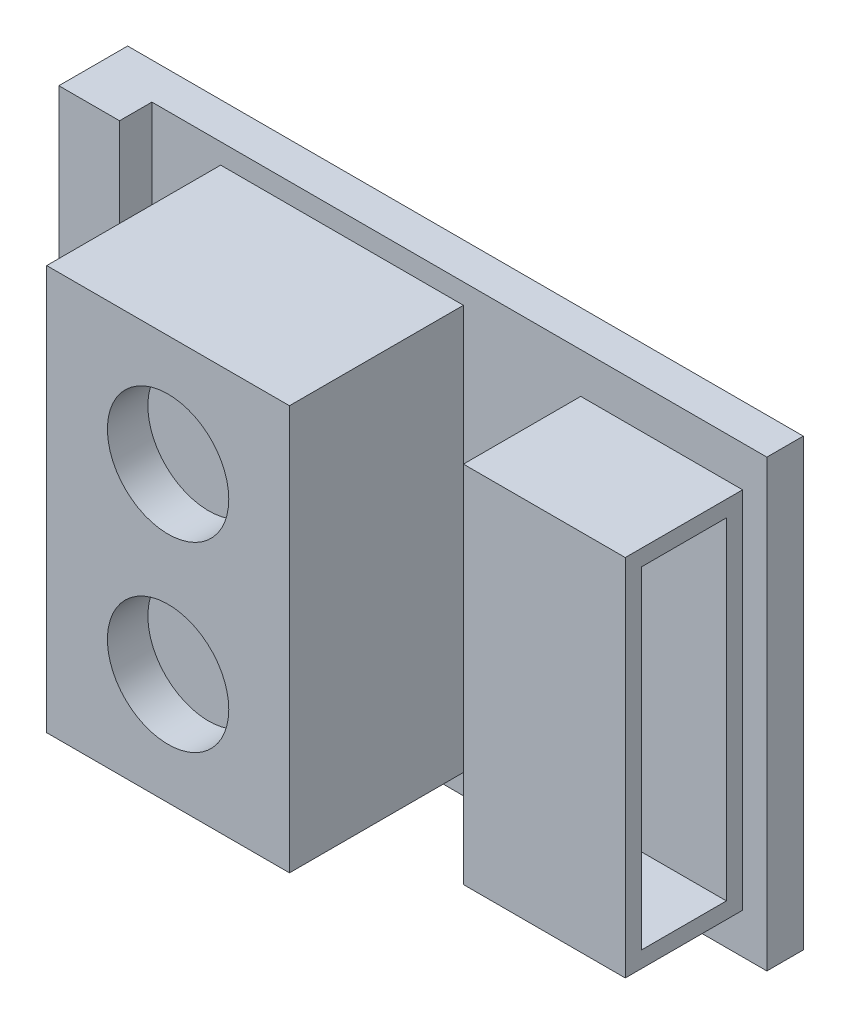
SolidWorks part; units mm, degrees
ref_plane "Plano frontal" through (0, 0, 0) normal (0, 0, 1) x (1, 0, 0)
ref_plane "Plano superior" through (0, 0, 0) normal (0, 1, 0) x (1, 0, 0)
ref_plane "Plano direito" through (0, 0, 0) normal (1, 0, 0) x (0, 0, -1)
sketch "Esboço1" plane through (0, 0, 0) normal (0, 0, 1) x (1, 0, 0)
  line L1 (-5.2816, 6.7404) -> (11.4184, 6.7404)
  line L2 (-5.2816, 6.7404) -> (-5.2816, -4.2596)
  line L3 (-5.2816, -4.2596) -> (11.4184, -4.2596)
  line L4 (11.4184, 6.7404) -> (11.4184, -4.2596)
  dimension "D1" = 16.7
  dimension "D2" = 11
extrude "Ressalto-extrusão1" add sketch "Esboço1" along normal blind 5.2
sketch "Esboço2" plane through (0, 0, 5.2) normal (0, 0, 1) x (1, 0, 0)
  line L0 (11.4184, 6.7404) -> (-5.2816, 6.7404) construction
  line L1 (-2.0816, 6.2404) -> (3.9184, 6.2404)
  line L2 (-2.0816, 6.2404) -> (-2.0816, -3.7596)
  line L3 (-2.0816, -3.7596) -> (3.9184, -3.7596)
  line L4 (3.9184, 6.2404) -> (3.9184, -3.7596)
  line L5 (6.8184, 5.7404) -> (10.8184, 5.7404)
  line L6 (6.8184, 5.7404) -> (6.8184, -3.2596)
  line L7 (6.8184, -3.2596) -> (10.8184, -3.2596)
  line L8 (10.8184, 5.7404) -> (10.8184, -3.2596)
  line L9 (-5.2816, -4.2596) -> (11.4184, -4.2596) construction
  line L10 (11.4184, -4.2596) -> (11.4184, 6.7404) construction
  line L12 (-5.2816, 6.7404) -> (11.4184, 6.7404)
  line L13 (-5.2816, 6.7404) -> (-5.2816, -4.2596)
  line L14 (-5.2816, -4.2596) -> (11.4184, -4.2596)
  line L15 (11.4184, 6.7404) -> (11.4184, -4.2596)
  point P12 (0.9184, -3.7596)
  dimension "D1" = 6
  dimension "D2" = 0.5
  dimension "D3" = 0.5
  dimension "D4" = 10.5
  dimension "D5" = 9
  dimension "D6" = 1
  dimension "D7" = 0.6
  dimension "D8" = 4
extrude "Corte-extrusão1" cut sketch "Esboço2" against normal blind 4.3
sketch "Esboço3" plane through (0, 0, 5.2) normal (0, 0, 1) x (1, 0, 0)
  line L1 (6.8184, 5.7404) -> (10.8184, 5.7404)
  line L2 (6.8184, 5.7404) -> (6.8184, -3.2596)
  line L3 (6.8184, -3.2596) -> (10.8184, -3.2596)
  line L4 (10.8184, 5.7404) -> (10.8184, -3.2596)
extrude "Corte-extrusão2" cut sketch "Esboço3" against normal blind 1.4
sketch "Esboço4" plane through (0, 0, 5.2) normal (0, 0, 1) x (1, 0, 0)
  line L0 (3.9184, 6.2404) -> (-2.0816, 6.2404) construction
  line L1 (-2.0816, -3.7596) -> (3.9184, -3.7596) construction
  circle A0 centre (0.9184, 3.4904) radius 1.5
  circle A1 centre (0.9184, -1.0096) radius 1.5
  dimension "D1" = 3
  dimension "D2" = 3
  dimension "D3" = 2.75
  dimension "D4" = 2.75
extrude "Corte-extrusão3" cut sketch "Esboço4" against normal blind 1
sketch "Esboço5" plane through (10.8184, 0, 0) normal (1, 0, 0) x (0, 0, -1)
  line L0 (-0.9, 5.7404) -> (-3.8, 5.7404) construction
  line L1 (-1.3, 5.3404) -> (-3.4, 5.3404)
  line L2 (-1.3, 5.3404) -> (-1.3, -2.8596)
  line L3 (-1.3, -2.8596) -> (-3.4, -2.8596)
  line L4 (-3.4, 5.3404) -> (-3.4, -2.8596)
  line L5 (-3.8, -3.2596) -> (-3.8, 5.7404) construction
  line L6 (-0.9, -3.2596) -> (-3.8, -3.2596) construction
  line L7 (-0.9, -4.2596) -> (-0.9, 6.7404) construction
  point P6 (-2.35, 5.7404)
  dimension "D1" = 0.4
  dimension "D2" = 0.4
  dimension "D3" = 0.4
  dimension "D4" = 0.4
extrude "Corte-extrusão4" cut sketch "Esboço5" against normal blind 3
sketch "Esboço6" plane through (0, 0, 0.9) normal (0, 0, 1) x (1, 0, 0)
  line L0 (-5.2816, -4.2596) -> (11.4184, -4.2596) construction
  line L1 (-5.2816, 6.7404) -> (-3.7816, 6.7404)
  line L2 (-5.2816, 6.7404) -> (-5.2816, -4.2596)
  line L3 (-5.2816, -4.2596) -> (-3.7816, -4.2596)
  line L4 (-3.7816, 6.7404) -> (-3.7816, -4.2596)
  dimension "D1" = 1.5
extrude "Ressalto-extrusão2" add sketch "Esboço6" along normal blind 0.8
